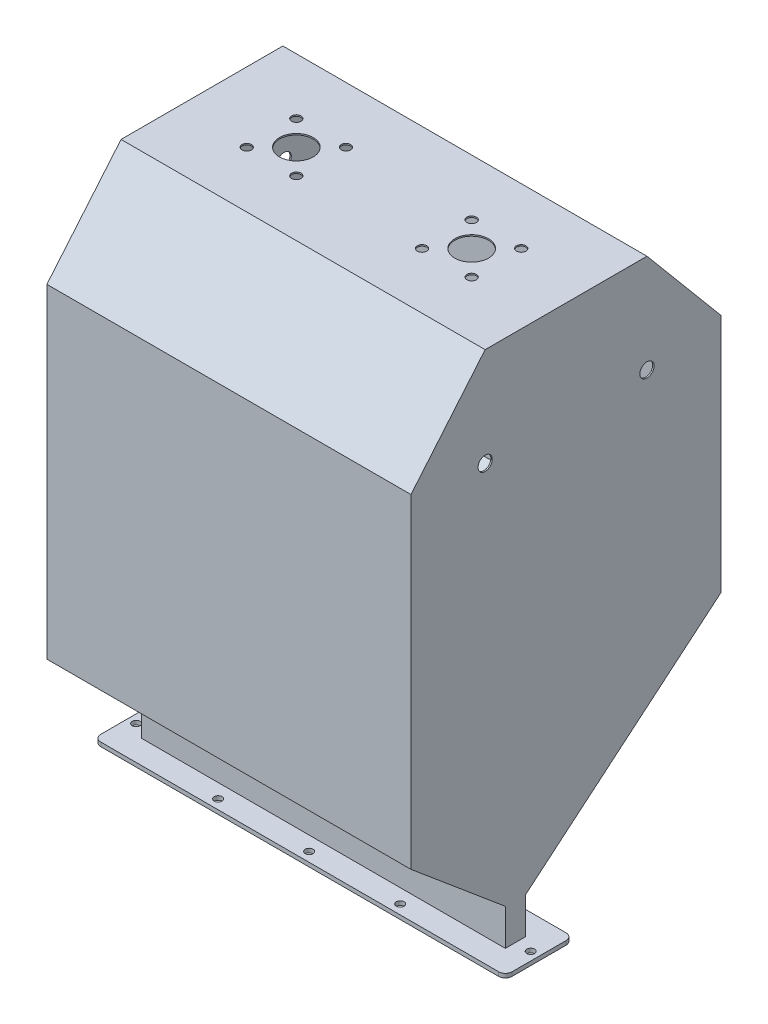
SolidWorks part; units mm, degrees
material "AISI Type 316L stainless steel"
ref_plane "Front Plane" through (0, 0, 0) normal (0, 0, 1) x (1, 0, 0)
ref_plane "Top Plane" through (0, 0, 0) normal (0, 1, 0) x (1, 0, 0)
ref_plane "Right Plane" through (0, 0, 0) normal (1, 0, 0) x (0, 0, -1)
sketch "Sketch1" plane through (0, 0, 0) normal (1, 0, 0) x (0, 0, -1)
  line L0 (-60, 236.8865) -> (60, 236.8865) construction
  line L1 (115, 171.34) -> (115, 0) construction
  line L2 (115, 0) -> (7.5, -128.1135) construction
  line L3 (7.5, -128.1135) -> (7.5, -158.1135) construction
  line L4 (7.5, -158.1135) -> (-7.5, -158.1135) construction
  line L5 (-7.5, -158.1135) -> (-7.5, -128.1135) construction
  line L6 (-7.5, -128.1135) -> (-115, 0) construction
  line L7 (-115, 0) -> (-115, 171.34) construction
  line L8 (0, -158.1135) -> (0, 0) construction
  line L9 (0, 0) -> (0, 236.8865) construction
  line L10 (-7.5, -128.1135) -> (-7.5, 82.8318) construction
  line L11 (-7.5, -128.1135) -> (7.5, -128.1135) construction
  line L12 (-115, 0) -> (115, 0) construction
  line L13 (-115, 171.34) -> (-115, -69.3765)
  line L14 (-115, -69.3765) -> (-45, -128.1135)
  line L15 (-45, -128.1135) -> (-45, -158.1135)
  line L16 (-45, -158.1135) -> (-30, -158.1135)
  line L17 (-30, -158.1135) -> (-30, -128.1135)
  line L18 (-30, -128.1135) -> (115, -6.4441)
  line L19 (115, -6.4441) -> (115, 171.34)
  line L20 (60, 236.8865) -> (-60, 236.8865)
  line L21 (-45, -128.1135) -> (-30, -128.1135) construction
  line L22 (-60, 236.8865) -> (-115, 171.34)
  line L23 (60, 236.8865) -> (115, 171.34)
  dimension "D1" = 365
  dimension "D2" = 40
  dimension "D3" = 15
  dimension "D4" = 30
  dimension "D5" = 230
  dimension "D6" = 15
  dimension "D7" = 50
  dimension "D8" = 70
  dimension "D9" = 50
  dimension "D10" = 60
  dimension "D11" = 50
sketch "Sketch7" plane through (0, 0, 0) normal (1, 0, 0) x (0, 0, -1)
  line L0 (-7.5, -158.1135) -> (-7.5, -128.1135) construction
  line L1 (-7.5, -128.1135) -> (-115, 0) construction
  line L2 (-115, 0) -> (-115, 171.34) construction
  line L3 (-7.5, -158.1135) -> (-7.5, -128.1135)
  line L4 (-7.5, -128.1135) -> (-115, 0)
  line L5 (-115, 0) -> (-115, 171.34)
  line L6 (-115, 171.34) -> (-116.5, 171.34)
  line L7 (-116.5, 171.34) -> (-116.5, -0.546)
  line L8 (-116.5, -0.546) -> (-9, -128.6595)
  line L9 (-9, -128.6595) -> (-9, -158.1135)
  line L10 (-9, -158.1135) -> (-7.5, -158.1135)
  dimension "D1" = 1.5
  dimension "D2" = 1.5
  dimension "D3" = 1.5
sketch "Sketch15" plane through (0, 0, 0) normal (1, 0, 0) x (0, 0, -1)
  line L0 (7.5, -128.1135) -> (7.5, -158.1135) construction
  line L1 (115, 0) -> (7.5, -128.1135) construction
  line L2 (115, 171.34) -> (115, 0) construction
  line L3 (7.5, -128.1135) -> (7.5, -158.1135)
  line L4 (115, 0) -> (7.5, -128.1135)
  line L5 (115, 171.34) -> (115, 0)
  line L6 (116.5, 171.34) -> (116.5, -0.546)
  line L7 (116.5, -0.546) -> (9, -128.6595)
  line L8 (9, -128.6595) -> (9, -158.1135)
  line L9 (115, 171.34) -> (116.5, 171.34)
  line L10 (7.5, -158.1135) -> (9, -158.1135)
  dimension "D1" = 1.5
extrude "Boss-Extrude1" add sketch "Sketch1" along normal mid plane 270
ref_plane "Plane1" through (0, 0, 37.5) normal (0, 0, 1) x (1, 0, 0)
shell "Shell1" thickness 1
sketch "Sketch16" plane through (0, -158.1135, 0) normal (0, -1, 0) x (1, 0, 0)
  line L0 (0, 30) -> (0, 37.5) construction
  line L1 (152.5, 62.5) -> (-152.5, 62.5)
  line L2 (152.5, 62.5) -> (152.5, 12.5)
  line L3 (152.5, 12.5) -> (-152.5, 12.5)
  line L4 (-152.5, 62.5) -> (-152.5, 12.5)
  line L5 (152.5, 62.5) -> (-152.5, 12.5) construction
  line L6 (152.5, 12.5) -> (-152.5, 62.5) construction
  line L7 (135, 30) -> (-135, 30) construction
  line L8 (0, 37.5) -> (-135, 37.5) construction
  line L9 (-135, 45) -> (-135, 30) construction
  line L10 (135, 45) -> (-135, 45) construction
  line L11 (135, 45) -> (135, 30) construction
  line L12 (-135, 45) -> (-135, 30)
  line L13 (135, 45) -> (-135, 45)
  line L14 (135, 30) -> (-135, 30)
  line L15 (135, 45) -> (135, 30)
  point P0 (0, 37.5)
  dimension "D1" = 50
  dimension "D2" = 305
extrude "Boss-Extrude2" add sketch "Sketch16" against normal blind 3 separate body
hole_wizard "M5 Clearance Hole1" positions "Sketch17" profile "Sketch18" hole size "M5" standard "ISO" end condition through all
sketch "Sketch17" plane through (0, -155.1135, 0) normal (0, 1, 0) x (1, 0, 0)
  circle A0 centre (146.3, -37.5) radius 2.1 construction
  circle A1 centre (0, -19.5) radius 2.1 construction
  point P0 (67.4925, -19.5)
  point P3 (0, -19.5)
  point P6 (-67.4925, -19.5)
  point P9 (-146.3, -37.5)
  point P12 (-67.4925, -55.5)
  point P15 (0, -55.5)
  point P18 (67.4925, -55.5)
  point P21 (146.3, -37.5)
sketch "Sketch18" plane through (67.4925, -155.1135, 19.5) normal (1, 0, 0) x (0, 0, 1)
  line L0 (0, 0) -> (0, 3)
  line L1 (0, 3) -> (2.9, 3)
  line L2 (2.9, 3) -> (2.9, 0)
  line L5 (2.9, 0) -> (0, 0)
  line L11 (0, -6.35) -> (0, 107.95) construction
  dimension "Thru Hole Dia." = 5.8
  dimension "Thru Hole Depth" = 3
sketch "Sketch19" plane through (0, 236.8865, 0) normal (0, 1, 0) x (1, 0, 0)
  line L0 (65, 0) -> (0, 0) construction
  line L1 (0, 0) -> (-65, 0) construction
  circle A0 centre (65, 0) radius 12.5
  circle A1 centre (-65, 0) radius 12.5
  dimension "D1" = 25
  dimension "D2" = 65
extrude "Cut-Extrude1" cut sketch "Sketch19" against normal blind 10
fillet "Fillet1" radius 5 4 edges at (-152.5, -156.6135, 12.5) (152.5, -156.6135, 12.5) (-152.5, -156.6135, 62.5) (152.5, -156.6135, 62.5)
hole_wizard "Ø7.0 (7) Diameter Hole1" positions "Sketch20" profile "Sketch22" hole size "Ø7.0" standard "ISO"
sketch "Sketch20" plane through (0, 236.8865, 0) normal (0, 1, 0) x (1, 0, 0)
  point P0 (46.6152, 18.3848)
  point P3 (83.3848, 18.3848)
  point P6 (46.6152, -18.3848)
  point P9 (83.3848, -18.3848)
sketch "Sketch22" plane through (46.6152, 236.8865, -18.3848) normal (1, 0, 0) x (0, 0, 1)
  line L0 (0, 0) -> (0, 22.103)
  line L1 (0, 22.103) -> (3.5, 20)
  line L2 (3.5, 20) -> (3.5, 0)
  line L5 (3.5, 0) -> (0, 0)
  line L10 (0, 22.103) -> (-3.5, 20) construction
  line L11 (0, -6.35) -> (0, 107.95) construction
  dimension "Hole Dia." = 7
  dimension "Hole Depth" = 20
  dimension "Drill Angle" = 118
mirror "Mirror1" about plane through (0, 0, 0) normal (1, 0, 0) of "Ø7.0 (7) Diameter Hole1"
sketch "Sketch23" plane through (0, -97.3383, -6.6765) normal (0, 0.766, 0.6428) x (1, 0, 0)
  line L0 (0, 57.4533) -> (0, -12.8778) construction
  line L1 (0, -12.8778) -> (0, -47.8778) construction
  line L3 (135, -47.8778) -> (-135, -47.8778) construction
  circle A0 centre (0, -12.8778) radius 7.4
  dimension "D1" = 14.8
  dimension "D2" = 35
extrude "Cut-Extrude2" cut sketch "Sketch23" along normal blind 10
hole_wizard "Ø10.5 (10.5) Diameter Hole1" positions "Sketch24" profile "Sketch25" hole size "Ø10.5" standard "ISO"
sketch "Sketch24" plane through (135, 0, 0) normal (1, 0, 0) x (0, 0, -1)
  point P0 (60, 163.8865)
  point P3 (-60, 163.8865)
sketch "Sketch25" plane through (135, 163.8865, -60) normal (0, 1, 0) x (0, 0, -1)
  line L0 (0, 0) -> (0, 8.1545)
  line L1 (0, 8.1545) -> (5.25, 5)
  line L2 (5.25, 5) -> (5.25, 0)
  line L5 (5.25, 0) -> (0, 0)
  line L10 (0, 8.1545) -> (-5.25, 5) construction
  line L11 (0, -6.35) -> (0, 107.95) construction
  dimension "Hole Dia." = 10.5
  dimension "Hole Depth" = 5
  dimension "Drill Angle" = 118
mirror "Mirror2" about plane through (0, 0, 0) normal (1, 0, 0) of "Ø10.5 (10.5) Diameter Hole1"
